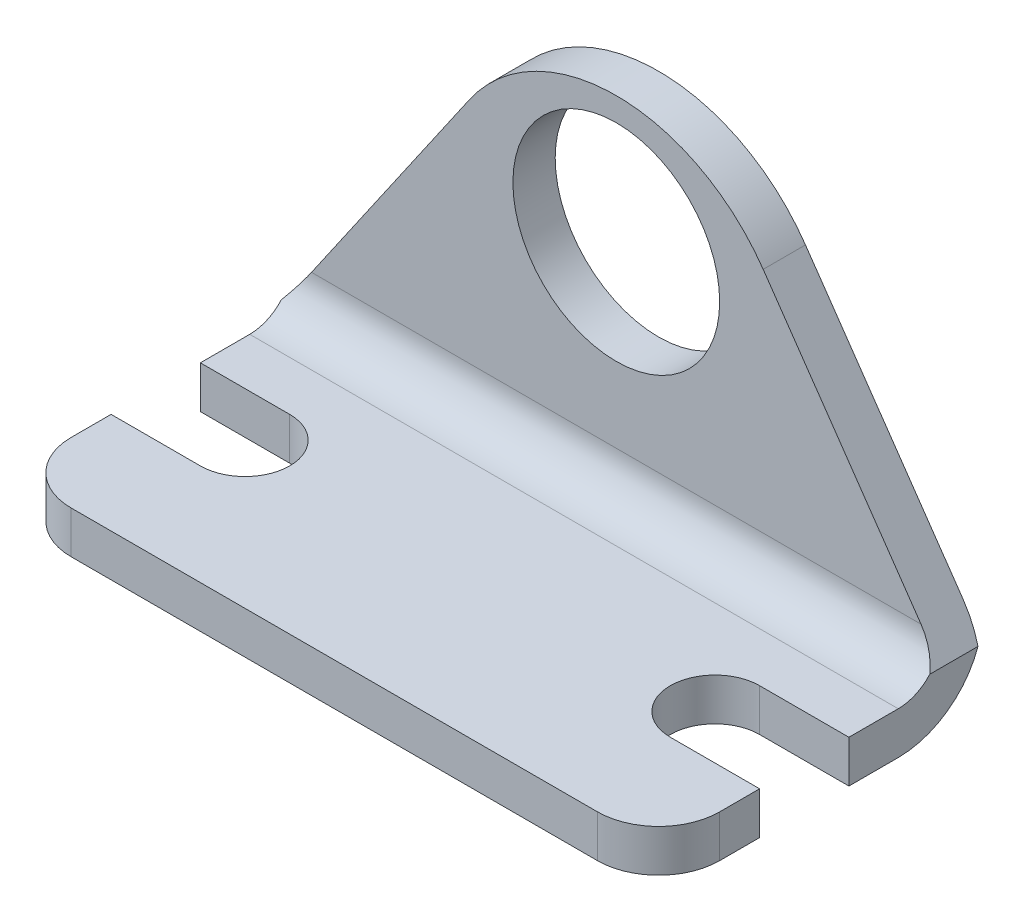
SolidWorks part; units mm, degrees
ref_plane "Front Plane" through (0, 0, 0) normal (0, 0, 1) x (1, 0, 0)
ref_plane "Top Plane" through (0, 0, 0) normal (0, 1, 0) x (1, 0, 0)
ref_plane "Right Plane" through (0, 0, 0) normal (1, 0, 0) x (0, 0, -1)
sketch "Sketch1" plane through (0, 0, 0) normal (0, 0, 1) x (1, 0, 0)
  line L0 (-17.526, 0) -> (17.526, 0)
  line L1 (17.526, 0) -> (17.526, 3.048)
  line L2 (17.526, 3.048) -> (7.9402, 16.9177)
  line L3 (-17.526, 0) -> (-17.526, 3.048)
  line L4 (-17.526, 3.048) -> (-7.9402, 16.9177)
  line L5 (-17.526, 3.048) -> (17.526, 3.048) construction
  line L6 (0, 14.224) -> (0, 0) construction
  line L7 (-17.526, 2.286) -> (17.526, 2.286) construction
  circle A0 centre (0, 14.224) radius 5.588
  arc A1 (7.9402, 16.9177) -> (-7.9402, 16.9177) centre (0, 11.43) ccw
extrude "Boss-Extrude1" add sketch "Sketch1" along normal blind 2.286
sketch "Sketch2" plane through (0, 0, 2.286) normal (0, 1, 0) x (1, 0, 0)
  line L0 (-12.7, -4.953) -> (-17.526, -4.953)
  line L1 (-17.526, 2.286) -> (17.526, 2.286)
  line L2 (-17.526, 2.286) -> (-17.526, -4.953)
  line L3 (-14.224, -15.24) -> (14.224, -15.24)
  line L4 (17.526, 2.286) -> (17.526, -4.953)
  line L5 (-12.7, -9.779) -> (-17.526, -9.779)
  line L6 (12.7, -9.779) -> (17.526, -9.779)
  line L7 (-17.526, -9.779) -> (-17.526, -11.938)
  line L8 (12.7, -4.953) -> (17.526, -4.953)
  line L9 (17.526, -9.779) -> (17.526, -11.938)
  line L10 (-12.7, -7.366) -> (12.7, -7.366) construction
  line L11 (0, 0) -> (0, -7.366) construction
  line L12 (-7.9402, 0) -> (7.9402, 0) construction
  arc A0 (-12.7, -9.779) -> (-12.7, -4.953) centre (-12.7, -7.366) ccw
  arc A1 (12.7, -4.953) -> (12.7, -9.779) centre (12.7, -7.366) ccw
  arc A2 (14.224, -15.24) -> (17.526, -11.938) centre (14.224, -11.938) ccw
  arc A3 (-17.526, -11.938) -> (-14.224, -15.24) centre (-14.224, -11.938) ccw
  point P28 (-17.526, -15.24)
  dimension "K" = 3.302
  dimension "C" = 17.526
  dimension "F" = 9.652
  dimension "E" = 4.826
  dimension "J" = 25.4
extrude "Boss-Extrude2" add sketch "Sketch2" along normal up to vertex (2.286 mm away) up to point (17.526, 2.286, 0)
fillet "Fillet1" radius 2.286 1 edges at (0, 2.286, 2.286)
fillet "Fillet2" radius 4.572 1 edges at (0, 0, 0)
equation "\"D1@Boss-Extrude1\" = \"H@Sketch1\""
equation "\"D1@Fillet1\" = \"H@Sketch1\""
equation "\"D1@Fillet2\"  = \"D1@Fillet1\" * 2"
